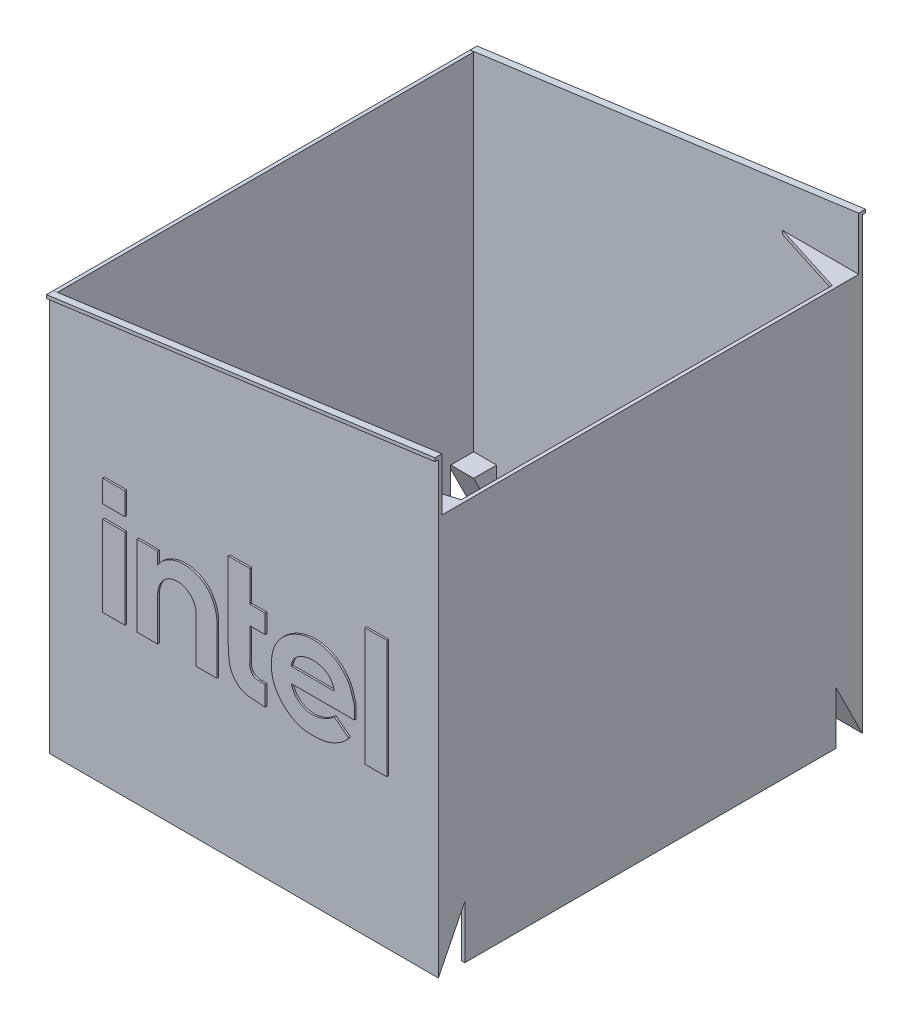
SolidWorks part; units mm, degrees
ref_plane "Front Plane" through (0, 0, 0) normal (0, 0, 1) x (1, 0, 0)
ref_plane "Top Plane" through (0, 0, 0) normal (0, 1, 0) x (1, 0, 0)
ref_plane "Right Plane" through (0, 0, 0) normal (1, 0, 0) x (0, 0, -1)
sketch "Sketch1" plane through (0, 0, 0) normal (0, 1, 0) x (1, 0, 0)
  line L1 (-110, 120) -> (110, 120)
  line L2 (-110, 120) -> (-110, -120)
  line L3 (-110, -120) -> (110, -120)
  line L4 (110, 120) -> (110, -120)
  line L5 (-110, 120) -> (110, -120) construction
  line L6 (-110, -120) -> (110, 120) construction
  point P0 (0, 0)
  dimension "D1" = 220
  dimension "D2" = 240
extrude "Extrude-Thin1" add sketch "Sketch1" along normal blind 226 thin contours L2 L1 L4 L3
sketch "Sketch2" plane through (0, 0, 0) normal (0, -1, 0) x (1, 0, 0)
  line L0 (-110, 120) -> (-95, 120)
  line L1 (-110, 120) -> (-110, 105)
  line L2 (-110, 105) -> (-95, 105)
  line L3 (-95, 120) -> (-95, 105)
  line L4 (95, 120) -> (110, 120)
  line L5 (95, 120) -> (95, 105)
  line L6 (95, 105) -> (110, 105)
  line L7 (110, 120) -> (110, 105)
  line L8 (-110, -105) -> (-95, -105)
  line L9 (-110, -105) -> (-110, -120)
  line L10 (-110, -120) -> (-95, -120)
  line L11 (-95, -105) -> (-95, -120)
  line L12 (95, -105) -> (110, -105)
  line L13 (95, -105) -> (95, -120)
  line L14 (95, -120) -> (110, -120)
  line L15 (110, -105) -> (110, -120)
extrude "Cut-Extrude1" cut sketch "Sketch2" against normal blind 5
sketch "Sketch4" plane through (0, 5, 0) normal (0, -1, 0) x (1, 0, 0)
  line L0 (95, 120) -> (110, 120)
  line L1 (95, 120) -> (95, 105)
  line L2 (95, 105) -> (110, 105)
  line L3 (110, 120) -> (110, 105)
  line L4 (-110, 120) -> (-95, 120)
  line L5 (-110, 120) -> (-110, 105)
  line L6 (-110, 105) -> (-95, 105)
  line L7 (-95, 120) -> (-95, 105)
  line L8 (-110, -105) -> (-95, -105)
  line L9 (-110, -105) -> (-110, -120)
  line L10 (-110, -120) -> (-95, -120)
  line L11 (-95, -105) -> (-95, -120)
  line L12 (95, -105) -> (110, -105)
  line L13 (95, -105) -> (95, -120)
  line L14 (95, -120) -> (110, -120)
  line L15 (110, -105) -> (110, -120)
sketch "Sketch6" plane through (0, 0, -120) normal (0, 0, -1) x (-1, 0, 0)
  line L0 (110, 226) -> (-110, 226)
  line L1 (-110, 226) -> (-110, 256)
  line L2 (-110, 256) -> (110, 226)
  dimension "D1" = 30
extrude "Boss-Extrude2" add sketch "Sketch6" against normal blind 2
sketch "Sketch7" plane through (0, 0, 120) normal (0, 0, 1) x (1, 0, 0)
  line L1 (110, 226) -> (110, 256)
  line L3 (110, 256) -> (-110, 226)
  line L4 (-110, 226) -> (110, 226)
extrude "Boss-Extrude3" add sketch "Sketch7" against normal blind 2
sketch "Sketch8" plane through (0, 0, 120) normal (0, 0, 1) x (1, 0, 0)
  line L0 (-110, 226) -> (110, 256)
  line L1 (110, 256) -> (110, 254.11)
  line L2 (110, 256) -> (110, 5) construction
  line L3 (110, 254.11) -> (-110, 224.11)
  line L4 (-110, 226) -> (-110, 5) construction
  line L5 (-110, 224.11) -> (-110, 226)
  dimension "D1" = 1.89
extrude "Boss-Extrude4" add sketch "Sketch8" along normal blind 1.89
sketch "Sketch9" plane through (0, 0, -120) normal (0, 0, -1) x (-1, 0, 0)
  line L1 (-110, 256) -> (-110, 254.11)
  line L4 (110, 224.11) -> (110, 226)
  line L5 (-110, 254.11) -> (110, 224.11)
  line L6 (110, 226) -> (-110, 256)
  dimension "D1" = 1.89
extrude "Boss-Extrude5" add sketch "Sketch9" along normal blind 1.89
sketch "Sketch10" plane through (0, 0, -120) normal (0, 0, -1) x (-1, 0, 0)
  line L0 (94.3279, 444.2012) -> (894.3279, 444.2012) construction
  line L1 (-18.0965, 106.0995) -> (-18.0965, 80.8416)
  line L2 (-82.7687, 146.6759) -> (-70.1287, 146.6759)
  line L3 (-82.7687, 146.6759) -> (-82.7687, 134.0359)
  line L4 (-82.7687, 134.0359) -> (-70.1287, 134.0359)
  line L5 (-70.1287, 146.6759) -> (-70.1287, 134.0359)
  line L6 (-82.7687, 126.4818) -> (-70.1287, 126.4818)
  line L7 (-82.7687, 126.4818) -> (-82.7687, 80.8416)
  line L8 (-82.7687, 80.8416) -> (-70.1287, 80.8416)
  line L9 (-70.1287, 126.4818) -> (-70.1287, 80.8416)
  line L10 (-63.2994, 126.4818) -> (-51.6177, 126.4818)
  line L11 (-63.2994, 126.4818) -> (-63.2994, 80.8416)
  line L12 (-63.2994, 80.8416) -> (-51.6177, 80.8416)
  line L14 (-18.0965, 80.8416) -> (-29.9059, 80.8416)
  line L15 (-29.9059, 80.8416) -> (-29.9059, 107.0561)
  line L16 (-51.6177, 126.4818) -> (-51.6177, 119.4775)
  line L17 (-51.6177, 80.8416) -> (-51.6177, 105.591)
  line L18 (0.5238, 97.7972) -> (0.5238, 115.8929)
  line L19 (0.5238, 115.8929) -> (9.2335, 115.8929)
  line L20 (9.2335, 115.8929) -> (9.2335, 126.4818)
  line L21 (9.2335, 126.4818) -> (0.5238, 126.4818)
  line L22 (0.5238, 126.4818) -> (0.5238, 144.0404)
  line L23 (0.5238, 144.0404) -> (-11.6654, 144.0404)
  line L24 (-11.6654, 144.0404) -> (-11.6654, 100.1685)
  line L25 (9.2335, 80.3368) -> (9.2335, 91.5545)
  line L26 (9.2335, 91.5545) -> (6.3246, 91.5545)
  line L27 (48.2737, 107.8216) -> (24.0669, 107.8216)
  line L28 (48.2737, 95.2241) -> (56.5309, 88.9451)
  line L29 (24.0669, 99.3004) -> (59.758, 99.3004)
  line L30 (65.7396, 147.5502) -> (78.094, 147.5502)
  line L31 (65.7396, 147.5502) -> (65.7396, 80.6532)
  line L32 (65.7396, 80.6532) -> (78.094, 80.6532)
  line L33 (78.094, 147.5502) -> (78.094, 80.6532)
  spline S0 degree 3 poles (-51.6177, 119.4775) (-50.422, 121.8672) (-46.7024, 124.9965) (-39.2237, 127.8998) (-31.3413, 127.272) (-20.5518, 121.8179) (-17.6462, 112.095) (-18.0965, 106.0995) knots 0 0 0 0 0.159974 0.285002 0.480268 0.619536 1 1 1 1
  spline S1 degree 3 poles (-29.9059, 107.0561) (-29.8978, 111.0006) (-35.0395, 118.3215) (-48.1759, 116.7578) (-51.3919, 109.2028) (-51.6177, 105.591) knots 0 0 0 0 0.356223 0.665401 1 1 1 1
  spline S2 degree 3 poles (-11.6654, 100.1685) (-11.5011, 96.4841) (-11.4992, 91.169) (-8.041, 84.928) (-3.7308, 81.4968) (0.3502, 80.848) (2.3279, 80.8416) knots 0 0 0 0 0.419622 0.554669 0.780328 1 1 1 1
  spline S3 degree 1 poles (2.3279, 80.8416) (9.2335, 80.3368) knots 0 0 1 1
  spline S4 degree 3 poles (6.3246, 91.5545) (5.0031, 91.4573) (2.6961, 91.7924) (0.7543, 94.58) (0.343, 96.4983) (0.5238, 97.7972) knots 0 0 0 0 0.424673 0.607236 1 1 1 1
  spline S5 degree 3 poles (24.0669, 107.8216) (24.2067, 109.2607) (25.0876, 112.2783) (28.5725, 115.1997) (32.4516, 116.5451) (36.3037, 117.0293) (40.391, 116.6212) (45.564, 114.3273) (48.0381, 110.5347) (48.2737, 107.8216) knots 0 0 0 0 0.131813 0.272597 0.391908 0.50059 0.62173 0.759762 1 1 1 1
  spline S6 degree 3 poles (24.0669, 99.3004) (25.4618, 93.8631) (30.2531, 90.3687) (39.3278, 89.6991) (45.4988, 92.4442) (48.2737, 95.2241) knots 0 0 0 0 0.510514 0.610514 1 1 1 1
  spline S7 degree 3 poles (56.5309, 88.9451) (55.0457, 86.5524) (50.969, 83.5206) (43.9031, 80.2592) (36.459, 79.8038) (28.2024, 80.3696) (20.479, 85.0097) (13.4072, 93.457) (11.9407, 104.9119) (15.9706, 118.651) (29.2641, 128.0534) (46.5935, 126.9073) (56.9884, 117.5092) (58.8132, 109.8026) (59.4614, 107.4011) knots 0 0 0 0 0.064713 0.115491 0.178952 0.235791 0.30517 0.381715 0.485059 0.557908 0.707957 0.817891 0.942015 1 1 1 1
  spline S8 degree 3 poles (59.4614, 107.4011) (59.8255, 106.3041) (59.6952, 103.5853) (59.8012, 100.8856) (59.758, 99.3004) knots 0 0 0 0 0.415978 1 1 1 1
  point P75 (77.9485, 126.4418)
  point P79 (0, 0)
  point P83 (78.094, 147.5502)
  dimension "D1" = 12.64
  dimension "D2" = 12.64
extrude "Boss-Extrude6" add sketch "Sketch10" along normal blind 1 separate body
sketch "Sketch14" plane through (0, 0, 120) normal (0, 0, 1) x (1, 0, 0)
  line L0 (98.0489, 448.6075) -> (898.0489, 448.6075) construction
  line L1 (-14.3755, 110.5058) -> (-14.3755, 85.2479)
  line L2 (-79.0477, 151.0822) -> (-66.4077, 151.0822)
  line L3 (-79.0477, 151.0822) -> (-79.0477, 138.4422)
  line L4 (-79.0477, 138.4422) -> (-66.4077, 138.4422)
  line L5 (-66.4077, 151.0822) -> (-66.4077, 138.4422)
  line L6 (-79.0477, 130.8881) -> (-66.4077, 130.8881)
  line L7 (-79.0477, 130.8881) -> (-79.0477, 85.2479)
  line L8 (-79.0477, 85.2479) -> (-66.4077, 85.2479)
  line L9 (-66.4077, 130.8881) -> (-66.4077, 85.2479)
  line L10 (-59.5783, 130.8881) -> (-47.8967, 130.8881)
  line L11 (-59.5783, 130.8881) -> (-59.5783, 85.2479)
  line L12 (-59.5783, 85.2479) -> (-47.8967, 85.2479)
  line L13 (-14.3755, 85.2479) -> (-26.1849, 85.2479)
  line L14 (-26.1849, 85.2479) -> (-26.1849, 111.4624)
  line L15 (-47.8967, 130.8881) -> (-47.8967, 123.8838)
  line L16 (-47.8967, 85.2479) -> (-47.8967, 109.9973)
  line L17 (4.2448, 102.2036) -> (4.2448, 120.2992)
  line L18 (4.2448, 120.2992) -> (12.9545, 120.2992)
  line L19 (12.9545, 120.2992) -> (12.9545, 130.8881)
  line L20 (12.9545, 130.8881) -> (4.2448, 130.8881)
  line L21 (4.2448, 130.8881) -> (4.2448, 148.4467)
  line L22 (4.2448, 148.4467) -> (-7.9444, 148.4467)
  line L23 (-7.9444, 148.4467) -> (-7.9444, 104.5749)
  line L24 (12.9545, 84.7432) -> (12.9545, 95.9608)
  line L25 (12.9545, 95.9608) -> (10.0456, 95.9608)
  line L26 (51.9947, 112.2279) -> (27.7879, 112.2279)
  line L27 (51.9947, 99.6304) -> (60.2519, 93.3514)
  line L28 (27.7879, 103.7067) -> (63.479, 103.7067)
  line L29 (69.4606, 151.9566) -> (81.815, 151.9566)
  line L30 (69.4606, 151.9566) -> (69.4606, 85.0595)
  line L31 (69.4606, 85.0595) -> (81.815, 85.0595)
  line L32 (81.815, 151.9566) -> (81.815, 85.0595)
  spline S0 degree 3 poles (-47.8967, 123.8838) (-46.7009, 126.2735) (-42.9813, 129.4028) (-35.5027, 132.3061) (-27.6203, 131.6783) (-16.8308, 126.2243) (-13.9252, 116.5014) (-14.3755, 110.5058) knots 0 0 0 0 0.159974 0.285002 0.480268 0.619536 1 1 1 1
  spline S1 degree 3 poles (-26.1849, 111.4624) (-26.1768, 115.4069) (-31.3185, 122.7278) (-44.4549, 121.1641) (-47.6709, 113.6091) (-47.8967, 109.9973) knots 0 0 0 0 0.356223 0.665401 1 1 1 1
  spline S2 degree 3 poles (-7.9444, 104.5749) (-7.78, 100.8904) (-7.7782, 95.5753) (-4.32, 89.3343) (-0.0098, 85.9032) (4.0712, 85.2543) (6.0489, 85.2479) knots 0 0 0 0 0.419622 0.554669 0.780328 1 1 1 1
  spline S3 degree 1 poles (6.0489, 85.2479) (12.9545, 84.7432) knots 0 0 1 1
  spline S4 degree 3 poles (10.0456, 95.9608) (8.7241, 95.8636) (6.4171, 96.1987) (4.4753, 98.9863) (4.064, 100.9046) (4.2448, 102.2036) knots 0 0 0 0 0.424673 0.607236 1 1 1 1
  spline S5 degree 3 poles (27.7879, 112.2279) (27.9277, 113.667) (28.8086, 116.6846) (32.2936, 119.6061) (36.1726, 120.9514) (40.0248, 121.4356) (44.1121, 121.0275) (49.285, 118.7336) (51.7591, 114.9411) (51.9947, 112.2279) knots 0 0 0 0 0.131813 0.272597 0.391908 0.50059 0.62173 0.759762 1 1 1 1
  spline S6 degree 3 poles (27.7879, 103.7067) (29.1828, 98.2694) (33.9741, 94.775) (43.0488, 94.1054) (49.2198, 96.8505) (51.9947, 99.6304) knots 0 0 0 0 0.510514 0.610514 1 1 1 1
  spline S7 degree 3 poles (60.2519, 93.3514) (58.7667, 90.9587) (54.69, 87.9269) (47.6242, 84.6655) (40.18, 84.2102) (31.9234, 84.7759) (24.2001, 89.416) (17.1282, 97.8633) (15.6618, 109.3182) (19.6916, 123.0573) (32.9852, 132.4597) (50.3146, 131.3136) (60.7094, 121.9155) (62.5343, 114.2089) (63.1825, 111.8074) knots 0 0 0 0 0.064713 0.115491 0.178952 0.235791 0.30517 0.381715 0.485059 0.557908 0.707957 0.817891 0.942015 1 1 1 1
  spline S8 degree 3 poles (63.1825, 111.8074) (63.5465, 110.7105) (63.4163, 107.9916) (63.5222, 105.2919) (63.479, 103.7067) knots 0 0 0 0 0.415978 1 1 1 1
extrude "Boss-Extrude7" add sketch "Sketch14" along normal blind 1
extrude "Cut-Extrude2" cut sketch "Sketch4" against normal blind 25
sketch "Sketch15" plane through (110, 0, 0) normal (1, 0, 0) x (0, 0, -1)
  line L0 (120, 30) -> (120, 0)
  line L1 (120, 30) -> (105, 30)
  line L2 (105, 30) -> (120, 0)
  line L3 (-120, 30) -> (-105, 30)
  line L4 (-105, 30) -> (-120, 0)
  line L5 (-120, 0) -> (-118, 0) construction
  line L6 (-120, 30) -> (-120, 0) construction
  line L7 (-120, 0) -> (-120, 30)
extrude "Boss-Extrude8" add sketch "Sketch15" against normal blind 15
sketch "Sketch16" plane through (-110, 0, 0) normal (-1, 0, 0) x (0, 0, 1)
  line L0 (105, 30) -> (120, 30)
  line L1 (120, 30) -> (120, 0)
  line L2 (120, 0) -> (105, 30)
  line L3 (-120, 30) -> (-120, 0)
  line L4 (-120, 30) -> (-120, 0) construction
  line L5 (-120, 0) -> (-105, 30)
  line L6 (-105, 30) -> (-120, 30)
extrude "Boss-Extrude9" add sketch "Sketch16" against normal blind 15
sketch "Sketch19" plane through (0, 226, 0) normal (0, 1, 0) x (1, 0, 0)
  line L0 (108, 105) -> (66.8214, 118)
  line L1 (66.8214, 118) -> (108, 118)
  line L2 (108, 118) -> (108, 105)
  line L3 (108, -105) -> (66.8214, -118)
  line L4 (66.8214, -118) -> (108, -118)
  line L5 (108, -118) -> (108, -105)
  line L6 (110, -118) -> (-110, -118) construction
  line L7 (-110, 118) -> (110, 118) construction
  point P10 (95, -118)
  point P13 (95, -118)
  point P14 (95, -118)
  point P15 (66.8214, -118)
  point P18 (57.5666, 118)
  point P21 (66.8214, 118)
extrude "Boss-Extrude10" add sketch "Sketch19" against normal blind 2
